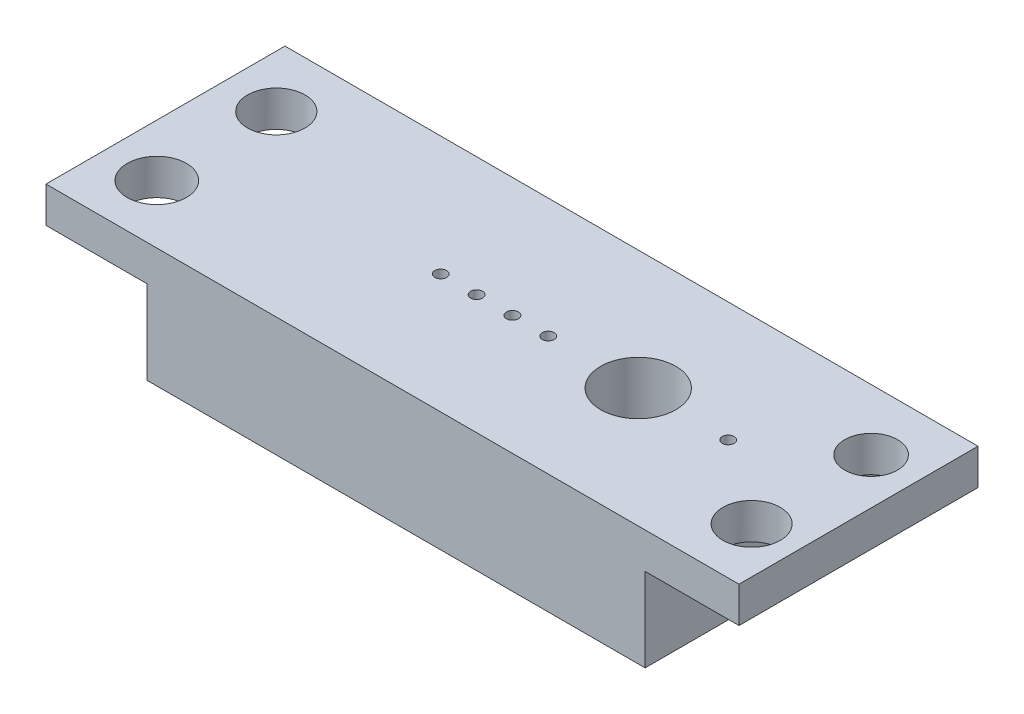
SolidWorks part; units mm, degrees
ref_plane "Ön Düzlem" through (0, 0, 0) normal (0, 0, 1) x (1, 0, 0)
ref_plane "Üst Düzlem" through (0, 0, 0) normal (0, 1, 0) x (1, 0, 0)
ref_plane "Sağ Düzlem" through (0, 0, 0) normal (1, 0, 0) x (0, 0, -1)
sketch "Sketch1" plane through (0, 0, 0) normal (0, 1, 0) x (1, 0, 0)
  line L1 (0, 0) -> (58, 0)
  line L2 (0, 0) -> (0, 20)
  line L3 (0, 20) -> (58, 20)
  line L4 (58, 0) -> (58, 20)
  dimension "D1" = 58
  dimension "D2" = 20
extrude "Boss-Extrude1" add sketch "Sketch1" along normal blind 3
sketch "Sketch2" plane through (0, 3, 0) normal (0, 1, 0) x (1, 0, 0)
  circle A0 centre (54.155, 14.8988) radius 2.2107
  circle A1 centre (54.155, 4.8988) radius 2.3998
  circle A2 centre (4.3757, 4.8988) radius 2.4788
  circle A3 centre (4.3757, 14.8988) radius 2.4039
extrude "Cut-Extrude1" cut sketch "Sketch2" against normal blind 10
sketch "Sketch3" plane through (0, 0, 0) normal (0, -1, 0) x (1, 0, 0)
  line L0 (0, 0) -> (58, 0) construction
  line L1 (50.1397, 0) -> (8.4328, 0)
  line L2 (50.1397, 0) -> (50.1397, -20)
  line L3 (50.1397, -20) -> (8.4328, -20)
  line L4 (8.4328, 0) -> (8.4328, -20)
  line L5 (58, -20) -> (0, -20) construction
extrude "Boss-Extrude2" add sketch "Sketch3" along normal up to surface (7 mm away)
sketch "Sketch4" plane through (0, 3, 0) normal (0, 1, 0) x (1, 0, 0)
  line L0 (-0.4347, -2.6012) -> (79.5653, -2.6012) construction
  line L1 (0, 20) -> (0, 0) construction
  circle A0 centre (39.5653, 10) radius 3.15
  point P5 (39.5653, -2.6012)
  point P9 (0, 10)
  dimension "D1" = 6.3
extrude "Cut-Extrude2" cut sketch "Sketch4" against normal blind 20
sketch "Sketch5" plane through (0, -7, 0) normal (0, -1, 0) x (1, 0, 0)
  circle A0 centre (26.0353, -10) radius 0.5
  circle A1 centre (29.0353, -10) radius 0.5
  circle A2 centre (23.0353, -10) radius 0.5
  circle A3 centre (32.0353, -10) radius 0.5
  circle A4 centre (47.0953, -10) radius 0.5
extrude "Cut-Extrude3" cut sketch "Sketch5" against normal blind 22
